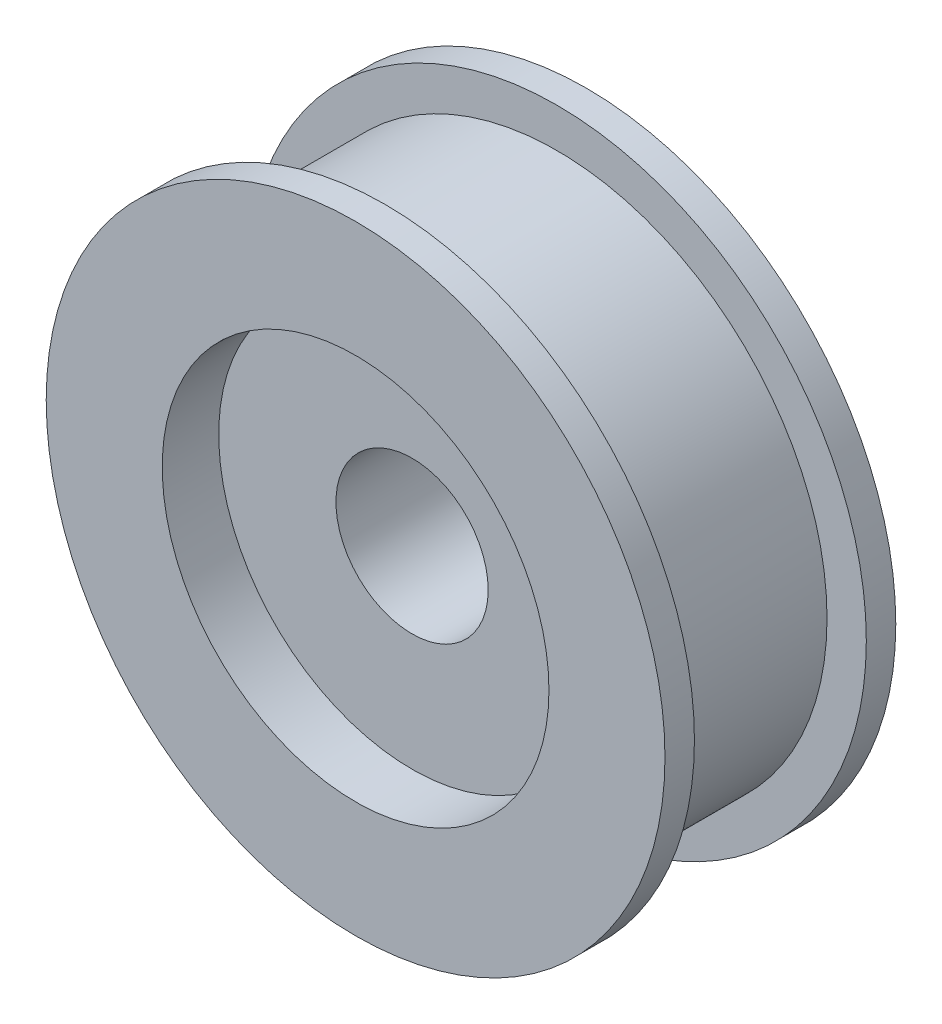
SolidWorks part; units mm, degrees
ref_plane "Plan de face" through (0, 0, 0) normal (0, 0, 1) x (1, 0, 0)
ref_plane "Plan de dessus" through (0, 0, 0) normal (0, 1, 0) x (1, 0, 0)
ref_plane "Plan de droite" through (0, 0, 0) normal (1, 0, 0) x (0, 0, -1)
sketch "Esquisse2" plane through (0, 0, 0) normal (0, 0, 1) x (1, 0, 0)
  circle A0 centre (0, 0) radius 3.1
  circle A1 centre (0, 0) radius 7.875
  dimension "D1" = 6.2
  dimension "D2" = 15.75
extrude "Boss.-Extru.1" add sketch "Esquisse2" along normal mid plane 4.8
sketch "Esquisse3" plane through (0, 0, 2.4) normal (0, 0, 1) x (1, 0, 0)
  circle A0 centre (0, 0) radius 12.6
  circle A1 centre (0, 0) radius 7.875
  circle A2 centre (0, 0) radius 7.875 construction
  dimension "D1" = 25.2
extrude "Boss.-Extru.2" add sketch "Esquisse3" along normal blind 2.3 and the other way blind 7.1
sketch "Esquisse4" plane through (0, 0, 0) normal (0, 0, 1) x (1, 0, 0)
  circle A0 centre (0, 0) radius 11
  circle A1 centre (0, 0) radius 12.6
  circle A2 centre (0, 0) radius 12.6 construction
  dimension "D1" = 22
extrude "Enlèv. mat.-Extru.1" cut sketch "Esquisse4" against normal mid plane 7
